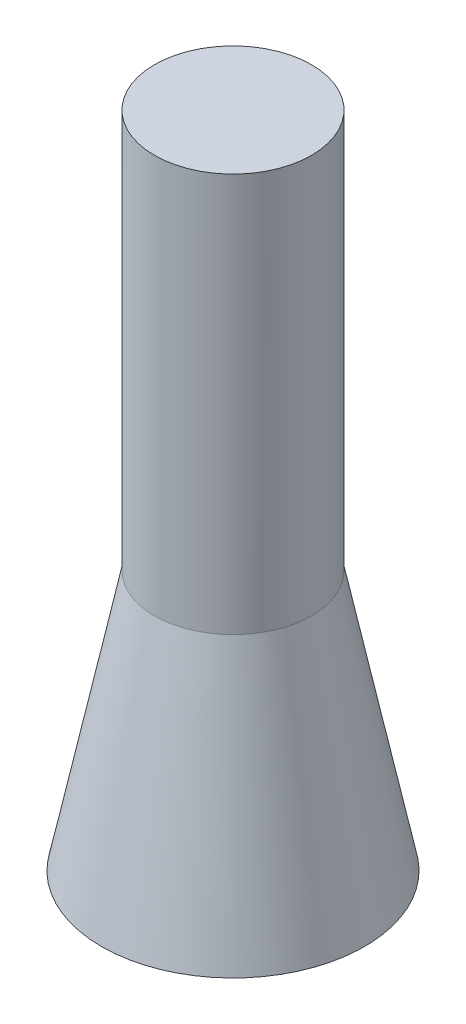
SolidWorks part; units mm, degrees
ref_plane "Front Plane" through (0, 0, 0) normal (0, 0, 1) x (1, 0, 0)
ref_plane "Top Plane" through (0, 0, 0) normal (0, 1, 0) x (1, 0, 0)
ref_plane "Right Plane" through (0, 0, 0) normal (1, 0, 0) x (0, 0, -1)
sketch "Sketch1" plane through (0, 0, 0) normal (0, 0, 1) x (1, 0, 0)
  line L3 (0, 0) -> (-10, 0)
  line L4 (-10, 0) -> (0, 48.9898)
  line L5 (0, 48.9898) -> (0, 0)
  dimension "D1" = 50
  dimension "D2" = 10
revolve "Revolve1" add sketch "Sketch1" angle 360 about L5
sketch "Sketch2" plane through (0, 0, 0) normal (0, 1, 0) x (1, 0, 0)
  circle A0 centre (0, 0) radius 5.969
  dimension "D1" = 11.938
extrude "Boss-Extrude1" add sketch "Sketch2" along normal blind 50.066 contours A0
sketch "Sketch7" plane through (0, 0, 0) normal (0, -1, 0) x (1, 0, 0)
  circle A0 centre (0, 0) radius 2.5
  dimension "D1" = 5
extrude "Cut-Extrude2" cut sketch "Sketch7" against normal blind 20
